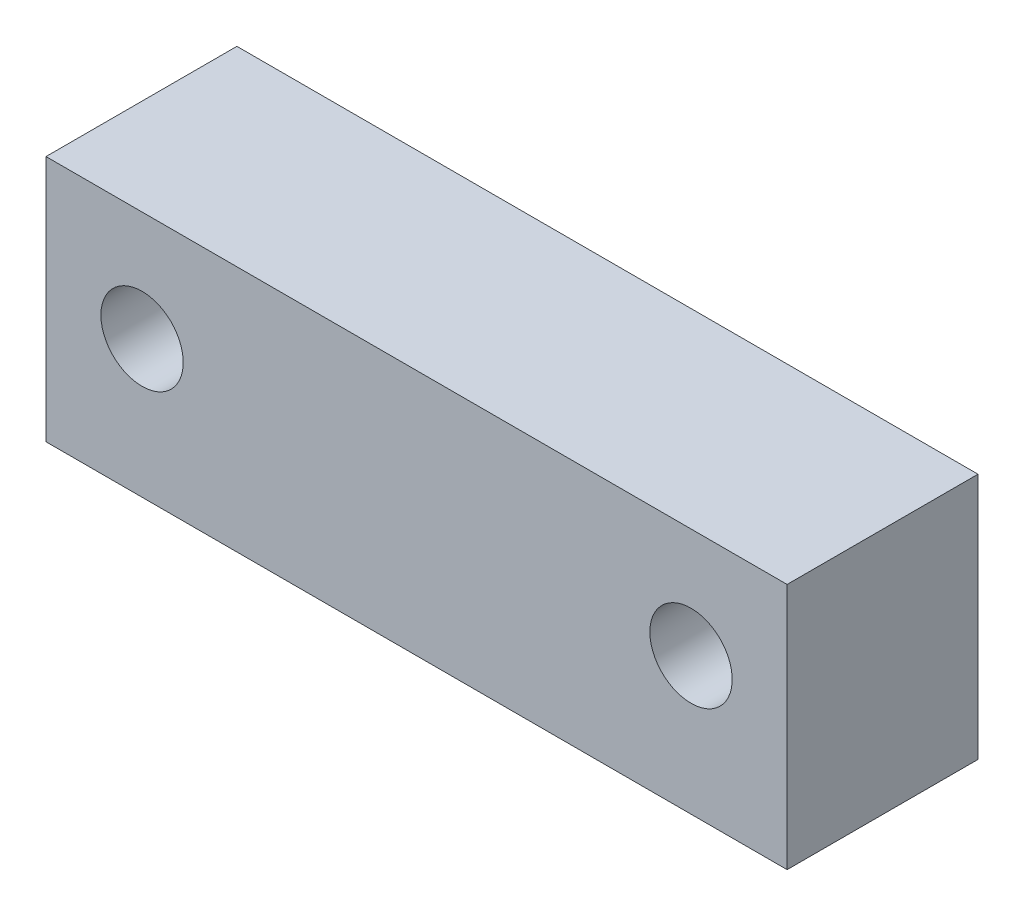
SolidWorks part; units mm, degrees
ref_plane "Plan de face" through (0, 0, 0) normal (0, 0, 1) x (1, 0, 0)
ref_plane "Plan de dessus" through (0, 0, 0) normal (0, 1, 0) x (1, 0, 0)
ref_plane "Plan de droite" through (0, 0, 0) normal (1, 0, 0) x (0, 0, -1)
sketch "Esquisse1" plane through (0, 0, 0) normal (0, 0, 1) x (1, 0, 0)
  line L0 (-27, 0) -> (27, 0)
  line L1 (-27, 0) -> (-27, -18)
  line L2 (27, 0) -> (27, -18)
  line L3 (-27, -18) -> (27, -18)
  circle A0 centre (-20, -8) radius 3
  circle A1 centre (20, -8) radius 3
  point P4 (0, 0)
  dimension "D4" = 6
  dimension "D1" = 54
  dimension "D2" = 18
  dimension "D3" = 18
  dimension "D5" = 7
  dimension "D6" = 8
  dimension "D7" = 2
extrude "Boss.-Extru.1" add sketch "Esquisse1" along normal blind 13.91
